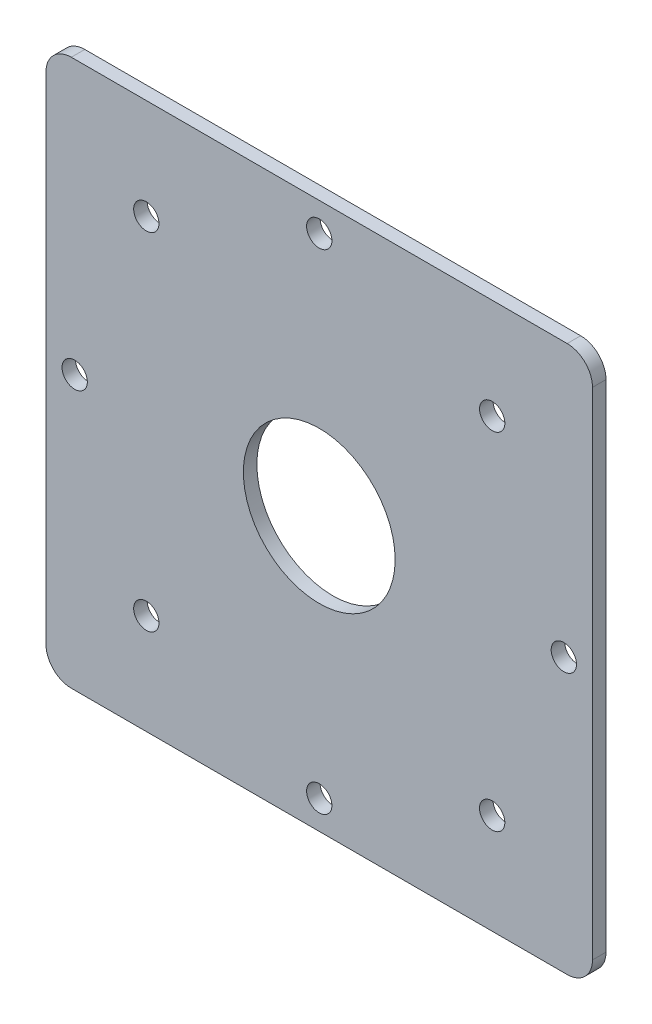
SolidWorks part; units mm, degrees
material "Plain Carbon Steel"
ref_plane "Front Plane" through (0, 0, 0) normal (0, 0, 1) x (1, 0, 0)
ref_plane "Top Plane" through (0, 0, 0) normal (0, 1, 0) x (1, 0, 0)
ref_plane "Right Plane" through (0, 0, 0) normal (1, 0, 0) x (0, 0, -1)
sketch "Sketch1" plane through (0, 0, 0) normal (0, 0, 1) x (1, 0, 0)
  line L1 (-162, -162) -> (162, -162)
  line L2 (-162, -162) -> (-162, 162)
  line L3 (-162, 162) -> (162, 162)
  line L4 (162, -162) -> (162, 162)
  line L5 (-162, -162) -> (162, 162) construction
  line L6 (-162, 162) -> (162, -162) construction
  point P0 (0, 0)
  dimension "D1" = 324
extrude "Boss-Extrude1" add sketch "Sketch1" along normal blind 8
sketch "Sketch2" plane through (0, 0, 8) normal (0, 0, 1) x (1, 0, 0)
  circle A0 centre (0, 0) radius 145 construction
  circle A1 centre (0, 145) radius 7.5
  dimension "D1" = 290
  dimension "D2" = 15
extrude "Cut-Extrude1" cut sketch "Sketch2" against normal blind 8
sketch "Sketch3" plane through (0, 0, 8) normal (0, 0, 1) x (1, 0, 0)
  circle A0 centre (0, 0) radius 45
  dimension "D1" = 90
extrude "Cut-Extrude2" cut sketch "Sketch3" against normal blind 10
pattern_circular "CirPattern1" count 8 over 360 about axis through (0, 0, 0) along (0, 0, 1) of "Cut-Extrude1"
fillet "Fillet1" radius 15 4 edges at (162, -162, 4) (162, 162, 4) (-162, 162, 4) (-162, -162, 4)
